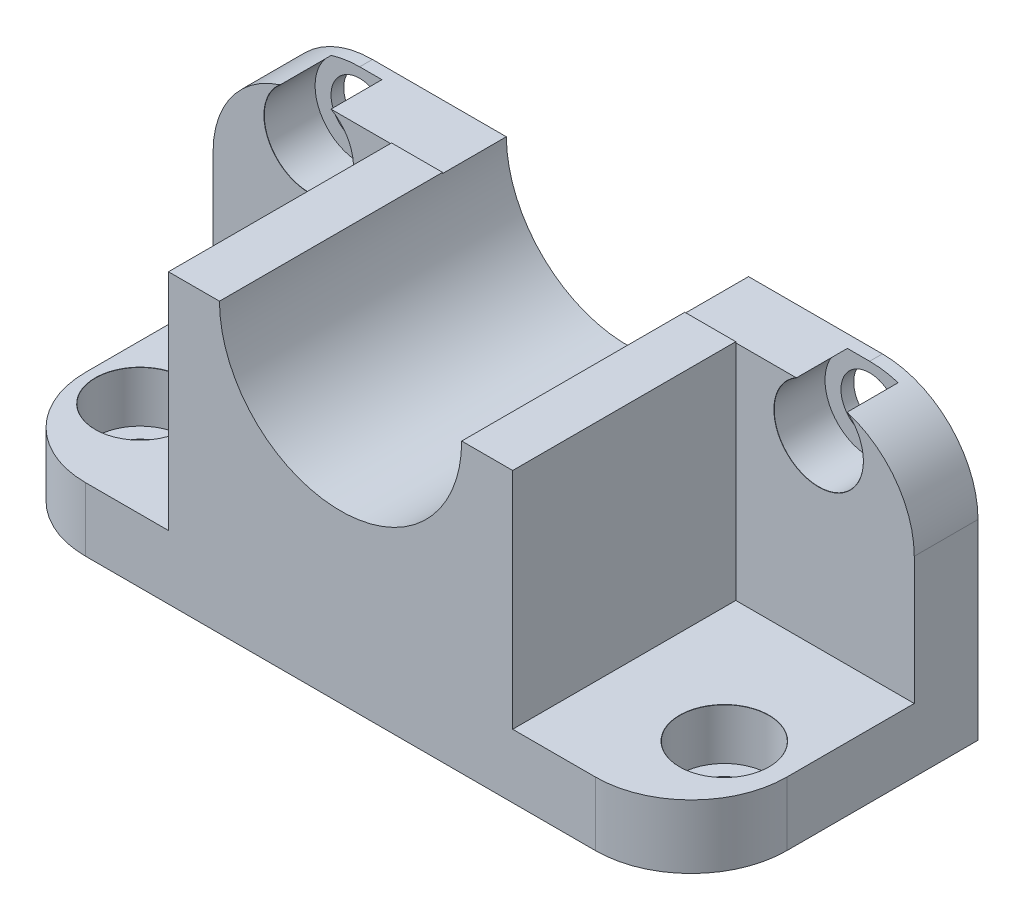
SolidWorks part; units mm, degrees
ref_plane "정면" through (0, 0, 0) normal (0, 0, 1) x (1, 0, 0)
ref_plane "윗면" through (0, 0, 0) normal (0, 1, 0) x (1, 0, 0)
ref_plane "우측면" through (0, 0, 0) normal (1, 0, 0) x (0, 0, -1)
sketch "스케치1" plane through (0, 0, 0) normal (0, 0, 1) x (1, 0, 0)
  line L0 (-55, 0) -> (55, 0)
  line L1 (55, 0) -> (55, 10)
  line L2 (55, 10) -> (27, 10)
  line L3 (27, 10) -> (27, 45.1589)
  line L4 (27, 45.1589) -> (-27, 45.1589)
  line L5 (-27, 45.1589) -> (-27, 10)
  line L6 (-27, 10) -> (-55, 10)
  line L7 (-55, 10) -> (-55, 0)
  dimension "D1" = 110
  dimension "D2" = 10
  dimension "D3" = 54
  dimension "D4" = 27
  dimension "D5" = 28
extrude "보스-돌출1" add sketch "스케치1" along normal blind 35
sketch "스케치2" plane through (0, 0, 0) normal (0, 0, -1) x (-1, 0, 0)
  line L1 (-55, 0) -> (55, 0)
  line L2 (-55, 0) -> (-55, 45)
  line L3 (-55, 45) -> (55, 45)
  line L4 (55, 0) -> (55, 45)
  dimension "D1" = 45
  dimension "D2" = 110
extrude "보스-돌출2" add sketch "스케치2" along normal blind 10
sketch "스케치3" plane through (0, 0, 35) normal (0, 0, 1) x (1, 0, 0)
  line L0 (27, 45.1589) -> (-27, 45.1589) construction
  line L1 (27, 45.1589) -> (-27, 45.1589)
  arc A0 (-16, 45.1589) -> (16, 45.1589) centre (0, 45.1589) ccw
  dimension "D2" = 32
extrude "컷-돌출1" cut sketch "스케치3" against normal through all and the other way through all contours A0
sketch "스케치4" plane through (0, 0, -10) normal (0, 0, -1) x (-1, 0, 0)
  line L0 (-19, 45.1589) -> (19, 45.1589)
  arc A0 (-19, 45.1589) -> (19, 45.1589) centre (0, 45.1589) ccw
  dimension "D1" = 38
extrude "컷-돌출2" cut sketch "스케치4" against normal blind 50
sketch "스케치6" plane through (0, 0, 0) normal (0, 0, 1) x (1, 0, 0)
  point P0 (-40, 38.9324)
  point P1 (40, 38.9324)
  dimension "D1" = 40
  dimension "D2" = 40
sketch "스케치7" plane through (0, 10, 0) normal (0, 1, 0) x (1, 0, 0)
  point P0 (-46.472, -20)
  point P1 (45.201, -20)
  dimension "D1" = 30
  dimension "D2" = 30
hole_wizard "M8 소켓 머리 캡 나사용 카운터보어5" positions "3D스케치5" profile "스케치12" counterbore size "M8" standard "KS" end condition through all
sketch3d "3D스케치5"
  point P0 (-40, 38.9324, 0)
sketch "스케치12" plane through (-40, 38.9324, 0) normal (1, 0, 0) x (0, -1, 0)
  line L0 (0, 0) -> (0, 10)
  line L1 (0, 10) -> (4.5, 10)
  line L3 (4.5, 10) -> (4.5, 8)
  line L4 (7, 8) -> (4.5, 8)
  line L5 (7, 8) -> (7, 0.0241)
  line L6 (7, 0.0241) -> (7.025, 0)
  line L7 (7.025, 0) -> (0, 0)
  line L8 (-7, 0.0241) -> (-7.025, 0) construction
  line L11 (0, -6.35) -> (0, 107.95) construction
  dimension "관통 구멍 지름" = 9
  dimension "관통 구멍 깊이" = 10
  dimension "카운터보어 지름" = 14
  dimension "카운터보어 깊이" = 8
  dimension "표면 카운터싱크 지름" = 14.05
  dimension "표면 카운터싱크 각도" = 92
hole_wizard "M8 소켓 머리 캡 나사용 카운터보어4" positions "3D스케치6" profile "스케치13" counterbore size "M8" standard "KS" end condition through all
sketch3d "3D스케치6"
  point P0 (-46.472, 10, 20)
sketch "스케치13" plane through (-46.472, 10, 20) normal (1, 0, 0) x (0, 0, 1)
  line L0 (0, 0) -> (0, 10)
  line L1 (0, 10) -> (4.5, 10)
  line L3 (4.5, 10) -> (4.5, 8)
  line L4 (7, 8) -> (4.5, 8)
  line L5 (7, 8) -> (7, 0.0241)
  line L6 (7, 0.0241) -> (7.025, 0)
  line L7 (7.025, 0) -> (0, 0)
  line L8 (-7, 0.0241) -> (-7.025, 0) construction
  line L11 (0, -6.35) -> (0, 107.95) construction
  dimension "관통 구멍 지름" = 9
  dimension "관통 구멍 깊이" = 10
  dimension "카운터보어 지름" = 14
  dimension "카운터보어 깊이" = 8
  dimension "표면 카운터싱크 지름" = 14.05
  dimension "표면 카운터싱크 각도" = 92
hole_wizard "M8 소켓 머리 캡 나사용 카운터보어3" positions "3D스케치8" profile "스케치15" counterbore size "M8" standard "KS" end condition through all
sketch3d "3D스케치8"
  point P0 (45.201, 10, 20)
sketch "스케치15" plane through (45.201, 10, 20) normal (1, 0, 0) x (0, 0, 1)
  line L0 (0, 0) -> (0, 10)
  line L1 (0, 10) -> (4.5, 10)
  line L3 (4.5, 10) -> (4.5, 8)
  line L4 (7, 8) -> (4.5, 8)
  line L5 (7, 8) -> (7, 0.0241)
  line L6 (7, 0.0241) -> (7.025, 0)
  line L7 (7.025, 0) -> (0, 0)
  line L8 (-7, 0.0241) -> (-7.025, 0) construction
  line L11 (0, -6.35) -> (0, 107.95) construction
  dimension "관통 구멍 지름" = 9
  dimension "관통 구멍 깊이" = 10
  dimension "카운터보어 지름" = 14
  dimension "카운터보어 깊이" = 8
  dimension "표면 카운터싱크 지름" = 14.05
  dimension "표면 카운터싱크 각도" = 92
hole_wizard "M8 소켓 머리 캡 나사용 카운터보어6" positions "3D스케치9" profile "스케치16" counterbore size "M8" standard "KS" end condition through all
sketch3d "3D스케치9"
  point P0 (40, 38.9324, 0)
sketch "스케치16" plane through (40, 38.9324, 0) normal (1, 0, 0) x (0, -1, 0)
  line L0 (0, 0) -> (0, 10)
  line L1 (0, 10) -> (4.5, 10)
  line L3 (4.5, 10) -> (4.5, 8)
  line L4 (7, 8) -> (4.5, 8)
  line L5 (7, 8) -> (7, 0.0241)
  line L6 (7, 0.0241) -> (7.025, 0)
  line L7 (7.025, 0) -> (0, 0)
  line L8 (-7, 0.0241) -> (-7.025, 0) construction
  line L11 (0, -6.35) -> (0, 107.95) construction
  dimension "관통 구멍 지름" = 9
  dimension "관통 구멍 깊이" = 10
  dimension "카운터보어 지름" = 14
  dimension "카운터보어 깊이" = 8
  dimension "표면 카운터싱크 지름" = 14.05
  dimension "표면 카운터싱크 각도" = 92
fillet "필렛2" radius 15 4 edges at (-55, 45, -5) (55, 45, -5) (55, 5, 35) (-55, 5, 35)
